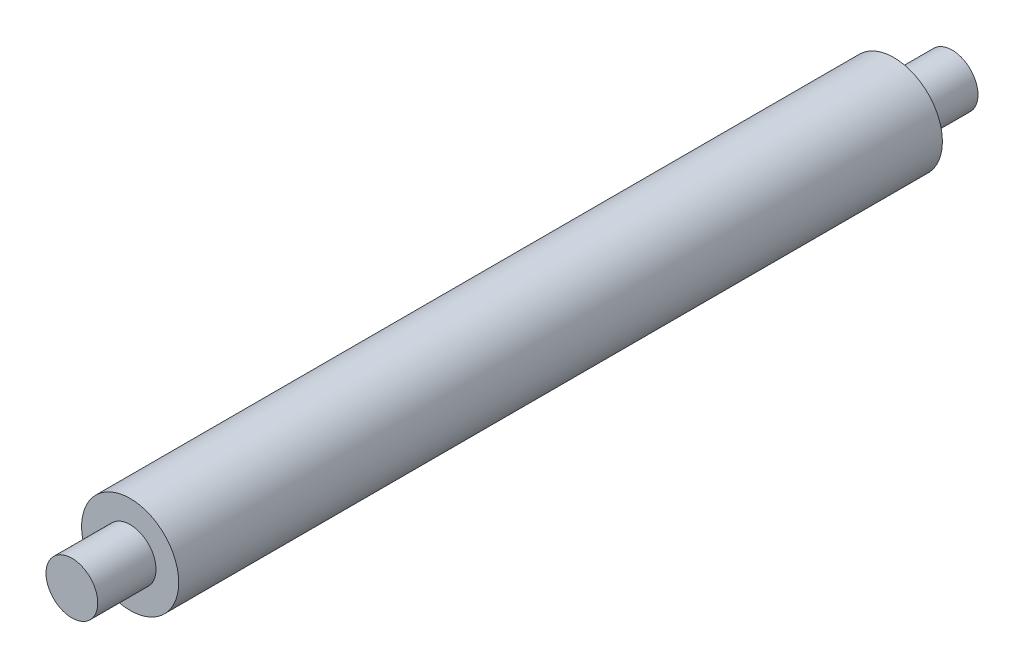
SolidWorks part; units mm, degrees
ref_plane "Front Plane" through (0, 0, 0) normal (0, 0, 1) x (1, 0, 0)
ref_plane "Top Plane" through (0, 0, 0) normal (0, 1, 0) x (1, 0, 0)
ref_plane "Right Plane" through (0, 0, 0) normal (1, 0, 0) x (0, 0, -1)
sketch "Sketch1" plane through (0, 0, 0) normal (0, 0, 1) x (1, 0, 0)
  circle A0 centre (0, 0) radius 37.5
  dimension "D1" = 75
extrude "Boss-Extrude1" add sketch "Sketch1" along normal mid plane 590
sketch "Sketch2" plane through (0, 0, 295) normal (0, 0, 1) x (1, 0, 0)
  circle A0 centre (0, 0) radius 20
  dimension "D1" = 40
extrude "Boss-Extrude2" add sketch "Sketch2" along normal blind 45
sketch "Sketch3" plane through (0, 0, -295) normal (0, 0, -1) x (-1, 0, 0)
  circle A0 centre (0, 0) radius 20
  dimension "D1" = 40
extrude "Boss-Extrude3" add sketch "Sketch3" along normal blind 45
